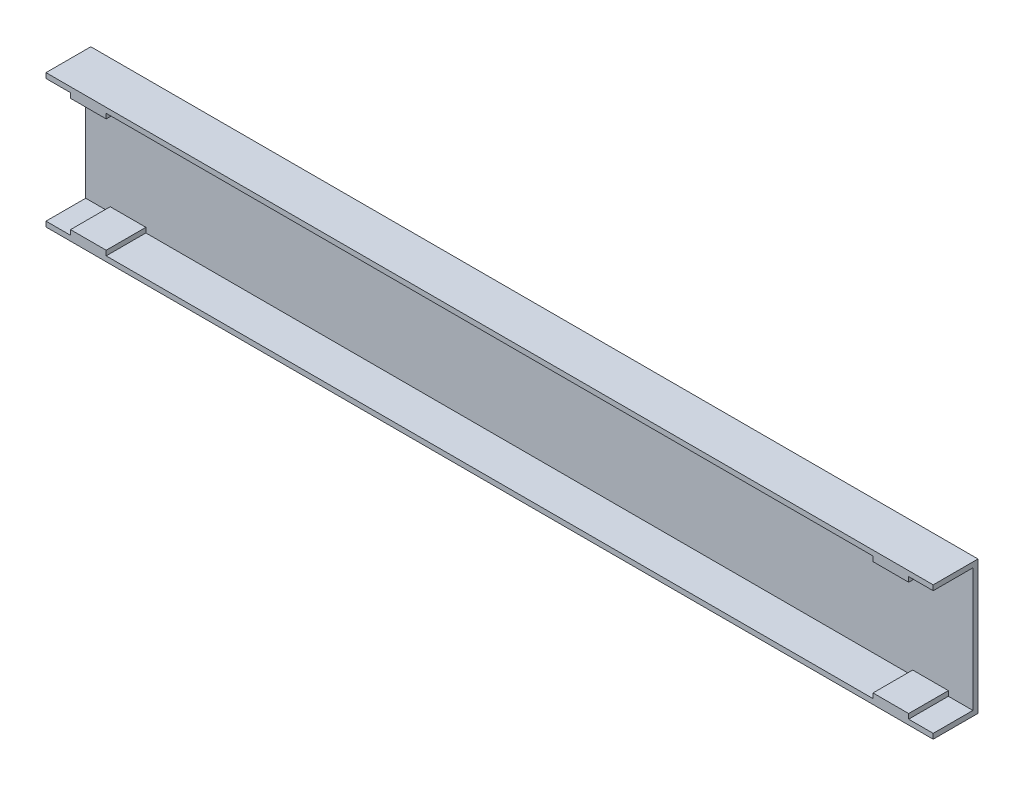
SolidWorks part; units mm, degrees
ref_plane "前视" through (0, 0, 0) normal (0, 0, 1) x (1, 0, 0)
ref_plane "上视" through (0, 0, 0) normal (0, 1, 0) x (1, 0, 0)
ref_plane "右视" through (0, 0, 0) normal (1, 0, 0) x (0, 0, -1)
sketch "草图1" plane through (0, 0, 0) normal (0, 0, 1) x (1, 0, 0)
  line L0 (0, 0) -> (0, 71.3124) construction
  line L1 (0, 71.3124) -> (0, 188.8094) construction
  line L2 (-995, 0) -> (995, 0)
  line L3 (-995, 0) -> (-995, 300)
  line L4 (-995, 300) -> (995, 300)
  line L5 (995, 0) -> (995, 300)
  line L6 (0, 188.8094) -> (0, 294.6471) construction
  line L7 (300, 294.6471) -> (300, -20.2744) construction
  line L8 (49.1838, 70) -> (952.4051, 70) construction
  line L9 (49.1838, 150) -> (1036.2895, 150) construction
  line L10 (49.1838, 230) -> (1036.2895, 230) construction
  dimension "D1" = 1990
  dimension "D2" = 300
  dimension "D3" = 300
  dimension "D4" = 70
  dimension "D5" = 80
  dimension "D6" = 80
extrude "基体-拉伸" add sketch "草图1" along normal blind 11.5
sketch "草图2" plane through (0, 0, 11.5) normal (0, 0, 1) x (1, 0, 0)
  line L0 (995, 0) -> (995, 300) construction
  line L1 (-995, 300) -> (995, 300)
  line L2 (-995, 300) -> (-995, 288.5)
  line L3 (-995, 288.5) -> (-940, 288.5)
  line L4 (995, 300) -> (995, 288.5)
  line L5 (472.8445, 150) -> (989.2832, 150) construction
  line L6 (-995, 0) -> (995, 0)
  line L7 (-995, 0) -> (-995, 11.5)
  line L8 (-995, 11.5) -> (-940, 11.5)
  line L9 (995, 0) -> (995, 11.5)
  line L10 (940, 288.5) -> (940, 277.5)
  line L11 (860, 11.5) -> (860, 22.5)
  line L12 (860, 22.5) -> (940, 22.5)
  line L13 (940, 11.5) -> (940, 22.5)
  line L14 (940, 11.5) -> (995, 11.5)
  line L15 (860, 288.5) -> (860, 277.5)
  line L16 (860, 277.5) -> (940, 277.5)
  line L17 (940, 288.5) -> (995, 288.5)
  line L18 (0, 0) -> (0, 280.097) construction
  line L19 (-940, 11.5) -> (-940, 22.5)
  line L20 (-860, 11.5) -> (-860, 22.5)
  line L21 (-860, 22.5) -> (-940, 22.5)
  line L22 (-940, 288.5) -> (-940, 277.5)
  line L23 (-860, 288.5) -> (-860, 277.5)
  line L24 (-860, 277.5) -> (-940, 277.5)
  line L25 (-860, 288.5) -> (860, 288.5)
  line L26 (-860, 11.5) -> (860, 11.5)
  dimension "D1" = 11.5
  dimension "D3" = 55
  dimension "D4" = 80
  dimension "D5" = 11
  dimension "D6" = 150
extrude "凸台-拉伸1" add sketch "草图2" along normal blind 89
sketch "草图7" plane through (0, 0, 0) normal (0, 0, -1) x (-1, 0, 0)
  line L0 (0, 0) -> (0, 358.9057) construction
  line L1 (265, 265) -> (335, 265)
  line L2 (265, 265) -> (265, 35)
  line L3 (265, 35) -> (335, 35)
  line L4 (335, 265) -> (335, 35)
  line L6 (995, 0) -> (-995, 0) construction
  line L7 (300, 333.2202) -> (300, -69.0551) construction
  line L8 (-335, 265) -> (-335, 35)
  line L9 (-265, 35) -> (-335, 35)
  line L10 (-265, 265) -> (-265, 35)
  line L11 (-265, 265) -> (-335, 265)
  circle A0 centre (300, 230) radius 13
  circle A1 centre (300, 150) radius 13
  circle A2 centre (300, 70) radius 13
  circle A3 centre (-300, 70) radius 13
  circle A4 centre (-300, 150) radius 13
  circle A5 centre (-300, 230) radius 13
  dimension "D6" = 26
  dimension "D1" = 265
  dimension "D2" = 70
  dimension "D3" = 230
  dimension "D4" = 35
  dimension "D5" = 35
  dimension "D7" = 70
  dimension "D8" = 80
  dimension "D9" = 80
extrude "凸台-拉伸2" add sketch "草图7" along normal blind 16
